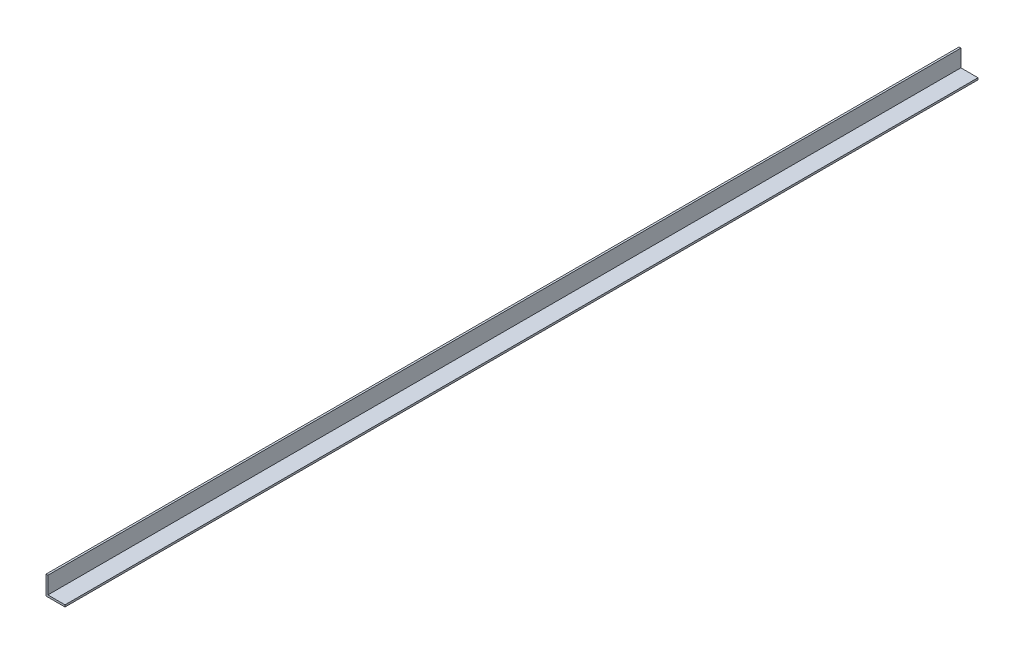
SolidWorks part; units mm, degrees
material "ASTM A36 Acero"
ref_plane "Alzado" through (0, 0, 0) normal (0, 0, 1) x (1, 0, 0)
ref_plane "Planta" through (0, 0, 0) normal (0, 1, 0) x (1, 0, 0)
ref_plane "Vista lateral" through (0, 0, 0) normal (1, 0, 0) x (0, 0, -1)
sketch "Croquis1" plane through (0, 0, 0) normal (0, 0, 1) x (1, 0, 0)
  line L0 (0, 127) -> (0, 0)
  line L1 (0, 0) -> (127, 0)
  line L2 (127, 0) -> (127, 12.7)
  line L3 (127, 12.7) -> (12.7, 12.7)
  line L4 (12.7, 12.7) -> (12.7, 127)
  line L5 (12.7, 127) -> (0, 127)
  dimension "D1" = 12.7
  dimension "D2" = 127
extrude "Saliente-Extruir1" add sketch "Croquis1" against normal blind 6100
